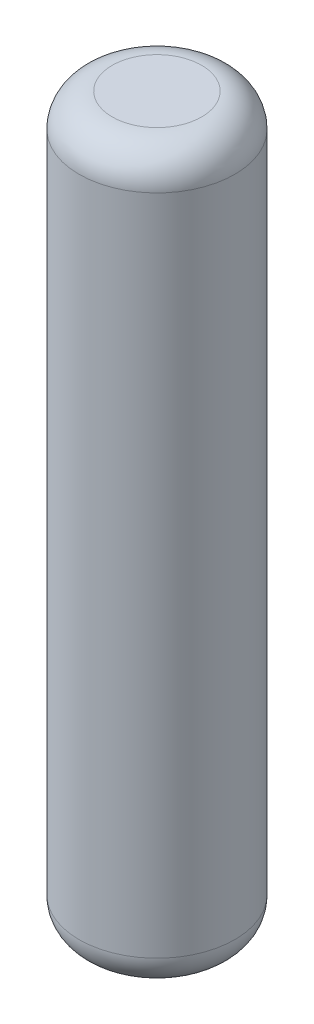
SolidWorks part; units mm, degrees
ref_plane "前视基准面" through (0, 0, 0) normal (0, 0, 1) x (1, 0, 0)
ref_plane "上视基准面" through (0, 0, 0) normal (0, 1, 0) x (1, 0, 0)
ref_plane "右视基准面" through (0, 0, 0) normal (1, 0, 0) x (0, 0, -1)
other "Configuration Table"
sketch "草图1" plane through (0, 0, 0) normal (0, 1, 0) x (1, 0, 0)
  circle A0 centre (0, 0) radius 2.35
  dimension "D1" = 4.7
extrude "凸台-拉伸1" add sketch "草图1" along normal blind 22
fillet "圆角1" radius 1 2 edges at (0, 0, 2.35) (0, 22, 2.35)
